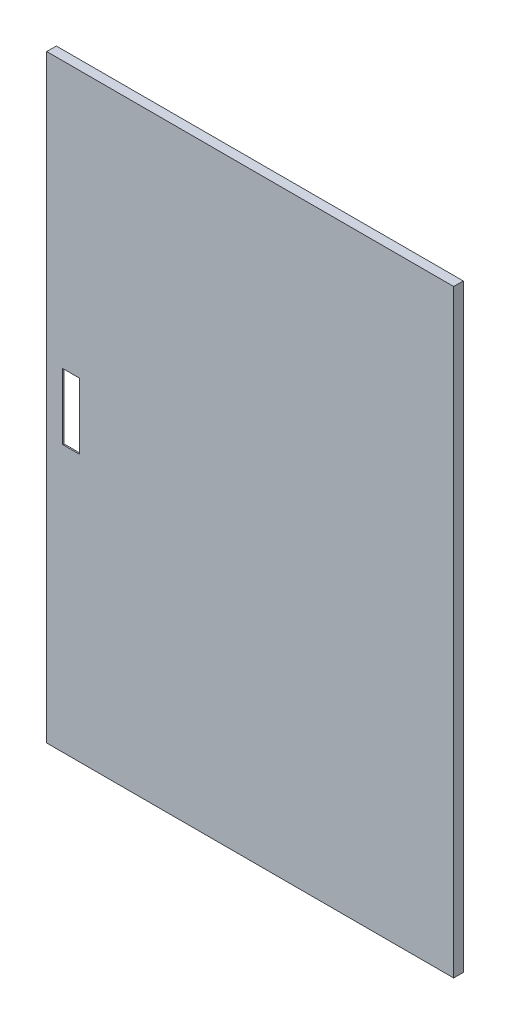
SolidWorks part; units mm, degrees
material "冷板"
ref_plane "前视基准面" through (0, 0, 0) normal (0, 0, 1) x (1, 0, 0)
ref_plane "上视基准面" through (0, 0, 0) normal (0, 1, 0) x (1, 0, 0)
ref_plane "右视基准面" through (0, 0, 0) normal (1, 0, 0) x (0, 0, -1)
sketch "草图1" plane through (0, 0, 0) normal (0, 0, 1) x (1, 0, 0)
  line L0 (0, 491.1739) -> (0, 0) construction
  line L1 (0, 0) -> (421.6954, 0) construction
  line L3 (-318, 468) -> (318, 468)
  line L4 (-318, 468) -> (-318, -468)
  line L5 (-318, -468) -> (318, -468)
  line L6 (318, 468) -> (318, -468)
  dimension "D1" = 636
  dimension "D2" = 936
extrude "凸台-拉伸1" add sketch "草图1" along normal blind 2
sketch "草图2" plane through (0, 0, 0) normal (0, 0, -1) x (-1, 0, 0)
  line L0 (0, 515.3034) -> (0, 0) construction
  line L1 (0, 0) -> (417.7311, 0) construction
  line L2 (316, -466) -> (316, 466)
  line L3 (316, 466) -> (-316, 466)
  line L4 (-316, 466) -> (-316, -466)
  line L5 (-316, -466) -> (316, -466)
  line L6 (318, -468) -> (318, 468)
  line L7 (318, 468) -> (-318, 468)
  line L8 (-318, 468) -> (-318, -468)
  line L9 (-318, -468) -> (318, -468)
  line L10 (318, -468) -> (318, 468)
  line L11 (318, 468) -> (-318, 468)
  line L12 (-318, 468) -> (-318, -468)
  line L13 (-318, -468) -> (318, -468)
  dimension "D1" = 0
  dimension "D2" = 2
extrude "凸台-拉伸2" add sketch "草图2" along normal blind 11
sketch "草图3" plane through (0, 0, -11) normal (0, 0, -1) x (-1, 0, 0)
  line L0 (-308, -458) -> (308, -458)
  line L1 (308, -458) -> (308, 458)
  line L2 (308, 458) -> (-308, 458)
  line L3 (-308, 458) -> (-308, -458)
  line L4 (-318, -468) -> (318, -468)
  line L5 (318, -468) -> (318, 468)
  line L6 (318, 468) -> (-318, 468)
  line L7 (-318, 468) -> (-318, -468)
  line L8 (-318, -468) -> (318, -468)
  line L9 (318, -468) -> (318, 468)
  line L10 (318, 468) -> (-318, 468)
  line L11 (-318, 468) -> (-318, -468)
  dimension "D1" = 0
  dimension "D2" = 10
extrude "凸台-拉伸3" add sketch "草图3" along normal blind 2
sketch "草图4" plane through (0, 0, 2) normal (0, 0, 1) x (1, 0, 0)
  line L0 (0, 473.4625) -> (0, 0) construction
  line L1 (0, 0) -> (-405.704, 0) construction
  line L2 (-318, 468) -> (-318, -468) construction
  line L3 (-293, 51.5) -> (-267, 51.5)
  line L4 (-293, 51.5) -> (-293, -51.5)
  line L5 (-293, -51.5) -> (-267, -51.5)
  line L6 (-267, 51.5) -> (-267, -51.5)
  dimension "D1" = 103
  dimension "D2" = 26
  dimension "D3" = 25
extrude "切除-拉伸1" cut sketch "草图4" against normal blind 10
